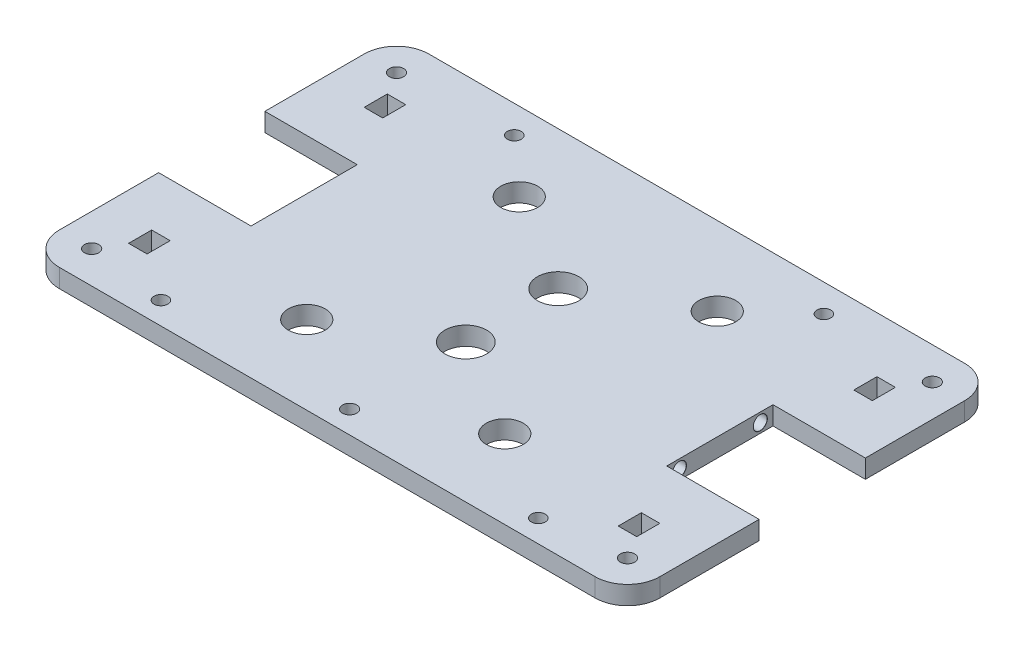
SolidWorks part; units mm, degrees
ref_plane "Front Plane" through (0, 0, 0) normal (0, 0, 1) x (1, 0, 0)
ref_plane "Top Plane" through (0, 0, 0) normal (0, 1, 0) x (1, 0, 0)
ref_plane "Right Plane" through (0, 0, 0) normal (1, 0, 0) x (0, 0, -1)
sketch "Sketch1" plane through (0, 0, 0) normal (0, 1, 0) x (1, 0, 0)
  line L0 (45, -11.5) -> (45, 11.5)
  line L1 (-58, -40) -> (58, -40)
  line L2 (-65, -33) -> (-65, -11.5)
  line L3 (-58, 40) -> (58, 40)
  line L4 (65, -33) -> (65, -11.5)
  line L5 (-65, -40) -> (65, 40) construction
  line L6 (-65, 40) -> (65, -40) construction
  line L8 (45, -11.5) -> (65, -11.5)
  line L9 (65, 11.5) -> (65, 33)
  line L10 (45, 11.5) -> (65, 11.5)
  line L15 (0, 0) -> (0, 29.598) construction
  line L16 (-45, -11.5) -> (-65, -11.5)
  line L18 (-45, 11.5) -> (-65, 11.5)
  line L23 (-65, 11.5) -> (-65, 33)
  line L24 (0, 0) -> (19.3136, 0) construction
  line L25 (55, -23) -> (51, -23)
  line L26 (55, -23) -> (55, -28)
  line L27 (55, -28) -> (51, -28)
  line L28 (51, -23) -> (51, -28)
  line L29 (55, 28) -> (51, 28)
  line L30 (51, 23) -> (51, 28)
  line L31 (55, 23) -> (51, 23)
  line L32 (55, 23) -> (55, 28)
  line L33 (-55, -28) -> (-51, -28)
  line L34 (-51, -23) -> (-51, -28)
  line L35 (-55, -23) -> (-51, -23)
  line L36 (-55, -23) -> (-55, -28)
  line L37 (-55, 23) -> (-55, 28)
  line L38 (-55, 23) -> (-51, 23)
  line L39 (-51, 23) -> (-51, 28)
  line L40 (-55, 28) -> (-51, 28)
  line L89 (-45, 11.5) -> (-45, -11.5)
  line L93 (-65, 40) -> (-65, -40) construction
  line L94 (-65, -40) -> (65, -40) construction
  line L95 (65, -40) -> (65, 40) construction
  line L96 (65, 40) -> (-65, 40) construction
  line L97 (-65, -40) -> (65, 40) construction
  line L98 (-65, 40) -> (65, -40) construction
  circle A0 centre (58, 33) radius 1.55
  circle A1 centre (58, -33) radius 1.55
  circle A2 centre (-58, -33) radius 1.55
  circle A3 centre (-58, 33) radius 1.55
  circle A4 centre (33.5, 34) radius 1.5
  arc A6 (42, 32.5) -> (42, 35.5) centre (42, 34) ccw construction
  arc A7 (25, 35.5) -> (25, 32.5) centre (25, 34) ccw construction
  circle A8 centre (-33.5, 34) radius 1.5
  circle A9 centre (-40.8473, -35.1576) radius 1.5
  arc A10 (-40.8211, -33.6578) -> (-40.8735, -36.6574) centre (-40.8473, -35.1576) ccw construction
  circle A11 centre (0, -35.1562) radius 1.55
  arc A12 (0, -33.6562) -> (0, -36.6562) centre (0, -35.1562) ccw construction
  circle A13 centre (40.8473, -35.1576) radius 1.5
  circle A14 centre (0, -10) radius 4.5
  circle A15 centre (0, 10) radius 4.5
  circle A16 centre (21.4348, -23) radius 4
  circle A17 centre (-21.4348, -23) radius 4
  circle A18 centre (-21.4348, 23) radius 4
  circle A19 centre (21.4348, 23) radius 4
  arc A20 (-58, -40) -> (-65, -33) centre (-58, -33) cw
  arc A21 (58, -40) -> (65, -33) centre (58, -33) ccw
  arc A22 (58, 40) -> (65, 33) centre (58, 33) cw
  arc A23 (-65, 33) -> (-58, 40) centre (-58, 33) cw
  point P0 (0, 0)
  point P101 (23.5, 34)
  dimension "D3" = 7
  dimension "D5" = 3.1
  dimension "D6" = 7
  dimension "D7" = 7
  dimension "D10" = 5
  dimension "D11" = 4
  dimension "D21" = 8.5
  dimension "D22" = 3
  dimension "D23" = 9
  dimension "D25" = 8
  dimension "D27" = 43.5652
  dimension "D28" = 7
  dimension "D1" = 80
  dimension "D2" = 130
  dimension "D4" = 7
  dimension "D8" = 20
  dimension "D9" = 23
  dimension "D12" = 5
  dimension "D13" = 3
  dimension "D20" = 28.5
  dimension "D24" = 10
  dimension "D26" = 17
extrude "Boss-Extrude1" add sketch "Sketch1" along normal blind 4
sketch "Szkic1" plane through (-45, 0, 0) normal (-1, 0, 0) x (0, 0, 1)
  line L0 (-11.5, 4) -> (-11.5, 0) construction
  line L1 (11.5, 4) -> (11.5, 0) construction
  line L2 (0, 0) -> (0, 4) construction
  line L3 (-11.5, 0) -> (11.5, 0) construction
  line L4 (-11.5, 4) -> (11.5, 4) construction
  line L5 (-8.75, 2) -> (8.75, 2) construction
  circle A0 centre (-8.75, 2) radius 1.5
  circle A1 centre (8.75, 2) radius 1.5
  point P13 (0, 2)
  point P14 (0, 0)
  point P17 (0, 0)
  dimension "D3" = 3
  dimension "D1" = 23
  dimension "D2" = 17.5
hole_wizard "Otwór Ø3.0 (3)1" positions "Szkic3" profile "Szkic5" hole size "Ø3.0" standard "ISO"
sketch "Szkic3" plane through (-45, 0, 0) normal (-1, 0, 0) x (0, 0, 1)
  point P0 (-8.75, 2)
  point P3 (8.75, 2)
sketch "Szkic5" plane through (-45, 2, -8.75) normal (0, 1, 0) x (0, 0, 1)
  line L0 (0, 0) -> (0, 20.9013)
  line L1 (0, 20.9013) -> (1.5, 20)
  line L2 (1.5, 20) -> (1.5, 0.025)
  line L3 (1.5, 0.025) -> (1.525, 0)
  line L5 (1.525, 0) -> (0, 0)
  line L6 (-1.5, 0.025) -> (-1.525, 0) construction
  line L10 (0, 20.9013) -> (-1.5, 20) construction
  line L11 (0, -6.35) -> (0, 107.95) construction
  dimension "Średnica otworu" = 3
  dimension "Głębokośc otworu" = 20
  dimension "Średnica zewnętrznego pogłębienia stożkowego" = 3.05
  dimension "Kąt zewnętrznego pogłębienia stożkowego" = 90
  dimension "Kąt wiertła" = 118
mirror "Lustro1" about plane through (0, 0, 0) normal (1, 0, 0) of "Otwór Ø3.0 (3)1"
